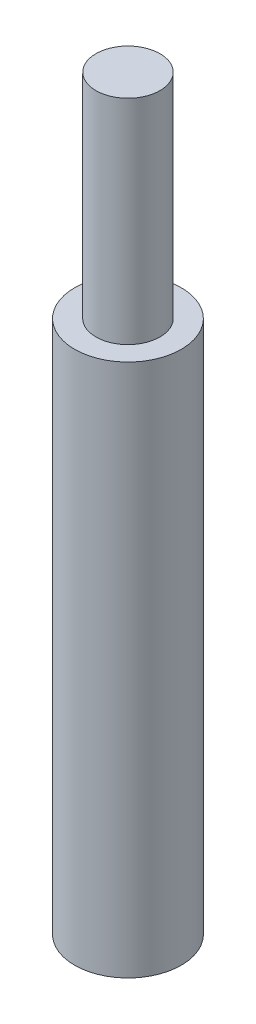
SolidWorks part; units mm, degrees
ref_plane "Front Plane" through (0, 0, 0) normal (0, 0, 1) x (1, 0, 0)
ref_plane "Top Plane" through (0, 0, 0) normal (0, 1, 0) x (1, 0, 0)
ref_plane "Right Plane" through (0, 0, 0) normal (1, 0, 0) x (0, 0, -1)
sketch "Sketch1" plane through (0, 0, 0) normal (0, 1, 0) x (1, 0, 0)
  circle A0 centre (0, 0) radius 2.5
  dimension "D1" = 5
extrude "Boss-Extrude1" add sketch "Sketch1" along normal blind 25
sketch "Sketch2" plane through (0, 25, 0) normal (0, 1, 0) x (1, 0, 0)
  circle A0 centre (0, 0) radius 2.5
sketch "Sketch3" plane through (0, 25, 0) normal (0, 1, 0) x (1, 0, 0)
  circle A0 centre (0, 0) radius 1.5
  dimension "D1" = 3
extrude "Boss-Extrude2" add sketch "Sketch3" along normal blind 10
